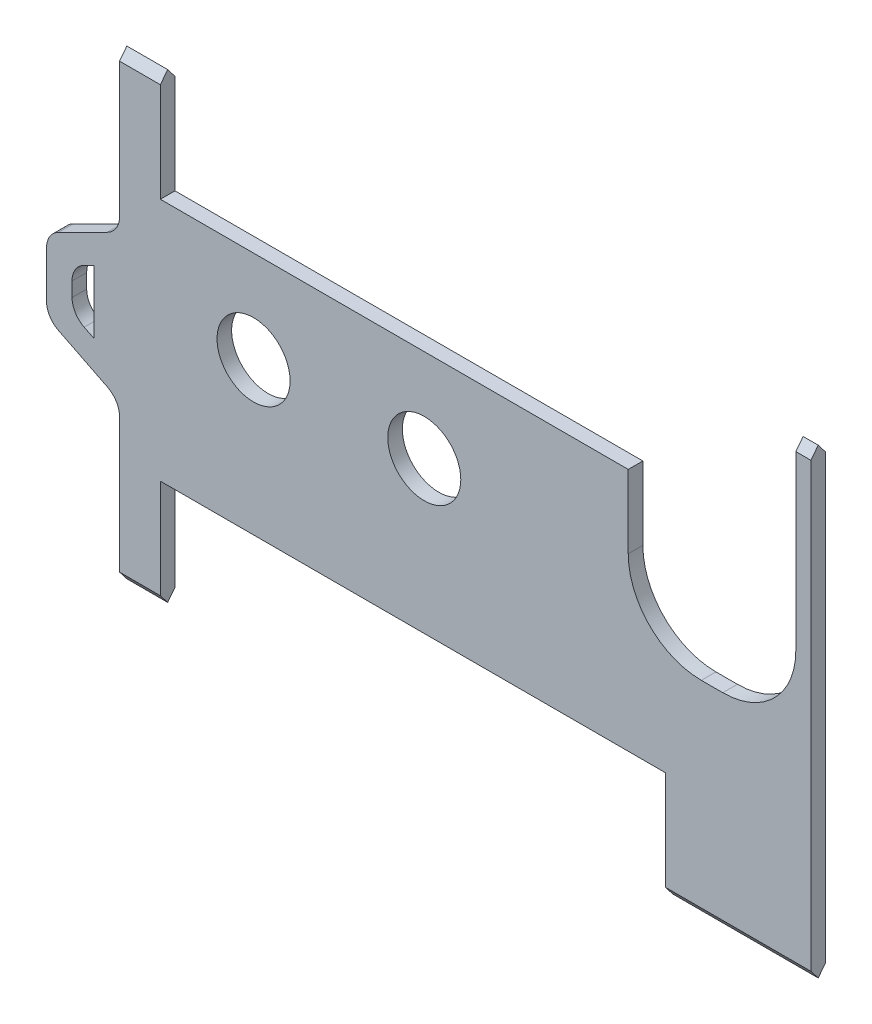
SolidWorks part; units mm, degrees
ref_plane "Front Plane" through (0, 0, 0) normal (0, 0, 1) x (1, 0, 0)
ref_plane "Top Plane" through (0, 0, 0) normal (0, 1, 0) x (1, 0, 0)
ref_plane "Right Plane" through (0, 0, 0) normal (1, 0, 0) x (0, 0, -1)
sketch "Sketch1" plane through (0, 0, 11.1483) normal (0, 0, 1) x (1, 0, 0)
  line L0 (22.4167, 106.8522) -> (12.4167, 101.8522)
  line L5 (22.2167, 125.2267) -> (22.2167, 68.4777) construction
  line L10 (12.4167, 101.8522) -> (12.4167, 91.8522)
  line L11 (117.2416, 128.7583) -> (22.2167, 128.7583) construction
  line L12 (117.2416, 128.7583) -> (117.2416, 64.9462) construction
  line L13 (117.2416, 64.9462) -> (22.2167, 64.9462) construction
  line L14 (22.2167, 128.7583) -> (22.2167, 64.9462) construction
  line L15 (117.0416, 128.5583) -> (22.4167, 128.5583)
  line L16 (22.4167, 128.5583) -> (22.4167, 65.1462)
  line L17 (117.0416, 65.1462) -> (22.4167, 65.1462)
  line L18 (117.0416, 128.5583) -> (117.0416, 65.1462)
  line L19 (12.4167, 91.8522) -> (22.4167, 86.8522)
  line L20 (92.0416, 128.5583) -> (92.0416, 93.5583)
  line L21 (92.0416, 93.5583) -> (117.0416, 93.5583)
  line L22 (114.9758, 128.5583) -> (114.9758, 93.5583)
  line L25 (22.4167, 106.8522) -> (22.4167, 86.8522)
  line L26 (15.9167, 94.0153) -> (18.9167, 92.5153)
  line L27 (18.9167, 101.1891) -> (18.9167, 92.5153)
  line L28 (18.9167, 101.1891) -> (15.9167, 99.6891)
  line L29 (15.9167, 99.6891) -> (15.9167, 94.0153)
  line L30 (-882.952, 96.8522) -> (49117.048, 96.8522) construction
  line L31 (28.0044, 130.2583) -> (28.0044, 127.2583) construction
  line L32 (28.0044, 128.5583) -> (97.1229, 128.5583)
  line L33 (28.0044, 128.5583) -> (28.0044, 113.5583)
  line L34 (28.0044, 113.5583) -> (97.1229, 113.5583)
  line L35 (97.1229, 128.5583) -> (97.1229, 113.5583)
  line L37 (97.1229, 130.2583) -> (97.1229, 127.2583) construction
  line L38 (28.0044, 80.1462) -> (97.1229, 80.1462)
  line L39 (97.1229, 65.1462) -> (97.1229, 80.1462)
  line L40 (28.0044, 65.1462) -> (97.1229, 65.1462)
  line L41 (28.0044, 65.1462) -> (28.0044, 80.1462)
  circle A0 centre (40.7588, 100.907) radius 5
  circle A1 centre (64.1228, 100.8815) radius 5
  point P4 (22.4167, 96.8522)
  point P8 (12.4167, 96.8522)
  point P34 (117.0416, 96.8522)
  dimension "D7" = 10
  dimension "D8" = 10
  dimension "D1" = 0.2
  dimension "D2" = 10
  dimension "D3" = 10
  dimension "D4" = 20
  dimension "D5" = 35
  dimension "D6" = 25
  dimension "D9" = 3.5
  dimension "D10" = 15
  dimension "D11" = 6.5
extrude "Boss-Extrude1" add sketch "Sketch1" along normal mid plane 2 contours L18 L15 L16 L17 | L10 L19 L16 L0 | L15 L22 L21 L18
sketch "Sketch2" plane through (22.4167, 0, 0) normal (-1, 0, 0) x (0, 0, 1)
  line L5 (-986.1517, 96.8522) -> (49013.8483, 96.8522) construction
  line L6 (13.8483, 68.4777) -> (13.8483, 125.2267) construction
  line L7 (10.1066, 128.5583) -> (10.1066, 127.0826)
  line L8 (12.19, 127.0826) -> (11.1483, 128.4311)
  line L10 (12.19, 66.6219) -> (12.19, 65.1462)
  line L11 (12.19, 65.1462) -> (10.1066, 65.1462)
  line L12 (11.1483, 65.2733) -> (10.1066, 66.6219)
  line L13 (12.19, 66.6219) -> (11.1483, 65.2733)
  line L14 (11.1483, 65.2733) -> (10.1066, 66.6219)
  line L15 (12.19, 66.6219) -> (11.1483, 65.2733)
  line L16 (10.1066, 65.1462) -> (10.1066, 66.6219)
  line L17 (12.1483, 65.1462) -> (10.1483, 65.1462) construction
  line L18 (11.1483, 128.4311) -> (10.1066, 127.0826)
  line L19 (12.19, 128.5583) -> (10.1066, 128.5583)
  line L20 (12.19, 127.0826) -> (12.19, 128.5583)
  point P9 (13.8483, 96.8522)
  dimension "D2" = 0.2
extrude "Cut-Extrude1" cut sketch "Sketch2" against normal through all
fillet "Fillet1" radius 10 2 edges at (92.0416, 93.5583, 11.1483) (114.9758, 93.5583, 11.1483)
fillet "Fillet2" radius 3 6 edges at (15.9167, 94.0153, 11.1483) (15.9167, 99.6891, 11.1483) (22.4167, 86.8522, 11.1483) (12.4167, 91.8522, 11.1483) (12.4167, 101.8522, 11.1483) (22.4167, 106.8522, 11.1483)
